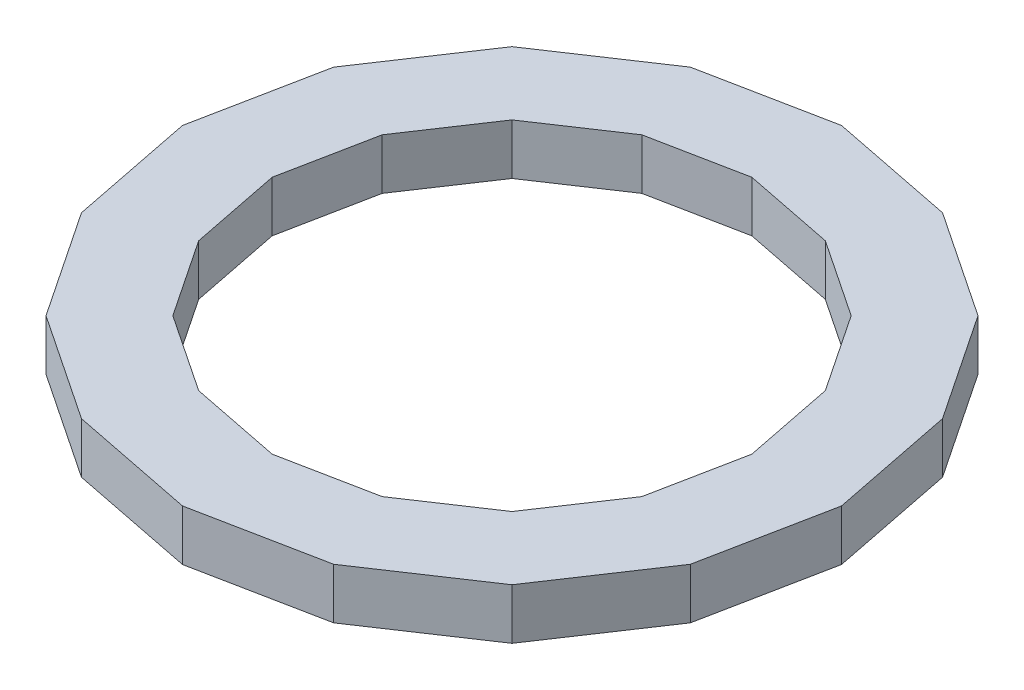
SolidWorks part; units mm, degrees
ref_plane "Front Plane" through (0, 0, 0) normal (0, 0, 1) x (1, 0, 0)
ref_plane "Top Plane" through (0, 0, 0) normal (0, 1, 0) x (1, 0, 0)
ref_plane "Right Plane" through (0, 0, 0) normal (1, 0, 0) x (0, 0, -1)
sketch "Sketch1" plane through (0, 0, 0) normal (0, 1, 0) x (1, 0, 0)
  line L1 (90.0194, 0) -> (83.1671, 34.4489)
  line L2 (83.1671, 34.4489) -> (63.6533, 63.6533)
  line L3 (63.6533, 63.6533) -> (34.4489, 83.1671)
  line L4 (34.4489, 83.1671) -> (0, 90.0194)
  line L5 (0, 90.0194) -> (-34.4489, 83.1671)
  line L6 (-34.4489, 83.1671) -> (-63.6533, 63.6533)
  line L7 (-63.6533, 63.6533) -> (-83.1671, 34.4489)
  line L8 (-83.1671, 34.4489) -> (-90.0194, 0)
  line L9 (-90.0194, 0) -> (-83.1671, -34.4489)
  line L10 (-83.1671, -34.4489) -> (-63.6533, -63.6533)
  line L11 (-63.6533, -63.6533) -> (-34.4489, -83.1671)
  line L12 (-34.4489, -83.1671) -> (0, -90.0194)
  line L13 (0, -90.0194) -> (34.4489, -83.1671)
  line L14 (34.4489, -83.1671) -> (63.6533, -63.6533)
  line L15 (63.6533, -63.6533) -> (83.1671, -34.4489)
  line L16 (83.1671, -34.4489) -> (90.0194, 0)
  line L17 (123.6863, 0) -> (114.2712, 47.3327)
  line L18 (114.2712, 47.3327) -> (87.4594, 87.4594)
  line L19 (87.4594, 87.4594) -> (47.3327, 114.2712)
  line L20 (47.3327, 114.2712) -> (0, 123.6863)
  line L21 (0, 123.6863) -> (-47.3327, 114.2712)
  line L22 (-47.3327, 114.2712) -> (-87.4594, 87.4594)
  line L23 (-87.4594, 87.4594) -> (-114.2712, 47.3327)
  line L24 (-114.2712, 47.3327) -> (-123.6863, 0)
  line L25 (-123.6863, 0) -> (-114.2712, -47.3327)
  line L26 (-114.2712, -47.3327) -> (-87.4594, -87.4594)
  line L27 (-87.4594, -87.4594) -> (-47.3327, -114.2712)
  line L28 (-47.3327, -114.2712) -> (0, -123.6863)
  line L29 (0, -123.6863) -> (47.3327, -114.2712)
  line L30 (47.3327, -114.2712) -> (87.4594, -87.4594)
  line L31 (87.4594, -87.4594) -> (114.2712, -47.3327)
  line L32 (114.2712, -47.3327) -> (123.6863, 0)
  circle A0 centre (0, 0) radius 88.2897 construction
  circle A1 centre (0, 0) radius 121.3097 construction
  dimension "D1" = 48.26
  dimension "D2" = 33.02
extrude "Boss-Extrude1" add sketch "Sketch1" along normal blind 19.05
